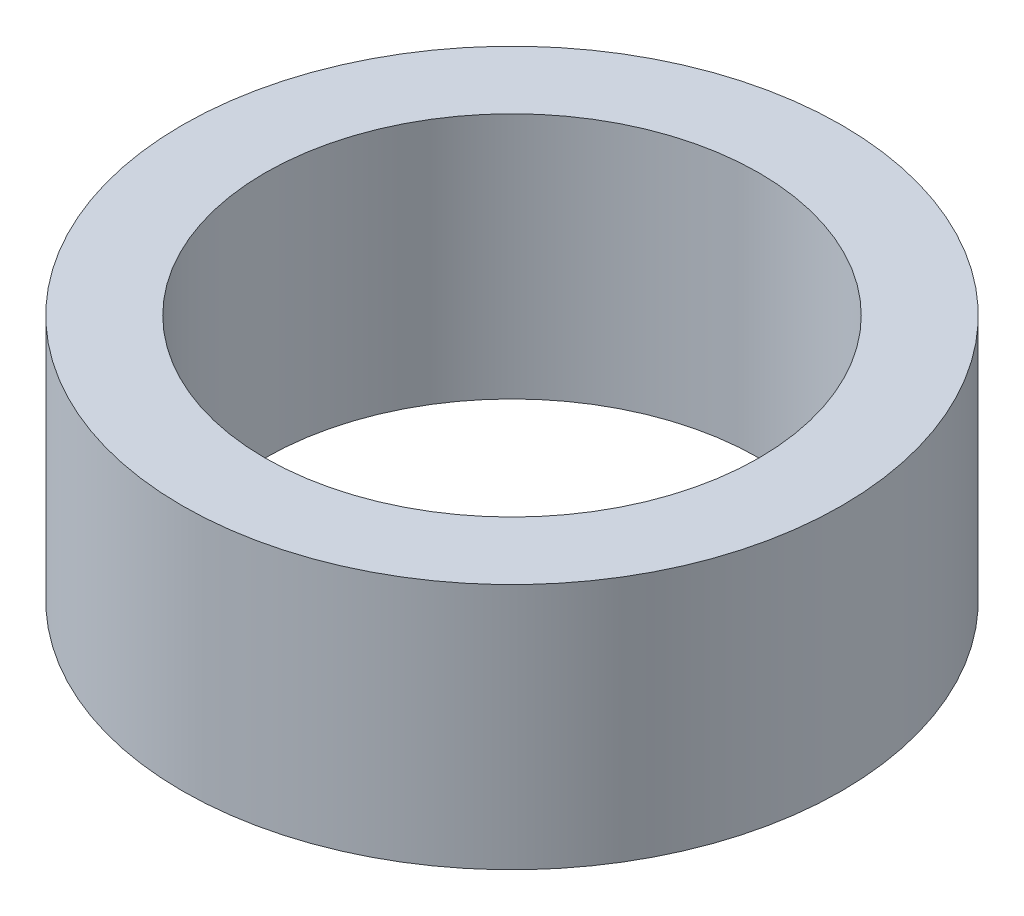
SolidWorks part; units mm, degrees
ref_plane "Alzado" through (0, 0, 0) normal (0, 0, 1) x (1, 0, 0)
ref_plane "Planta" through (0, 0, 0) normal (0, 1, 0) x (1, 0, 0)
ref_plane "Vista lateral" through (0, 0, 0) normal (1, 0, 0) x (0, 0, -1)
sketch "Croquis1" plane through (0, 0, 0) normal (0, 1, 0) x (1, 0, 0)
  circle A0 centre (0, 0) radius 13.35
  dimension "D1" = 26.7
extrude "Saliente-Extruir3" add sketch "Croquis1" along normal blind 10
sketch "Croquis4" plane through (0, 0, 0) normal (0, 1, 0) x (1, 0, 0)
  circle A0 centre (0, 0) radius 10
  dimension "D1" = 20
extrude "Cortar-Extruir1" cut sketch "Croquis4" along normal blind 12
